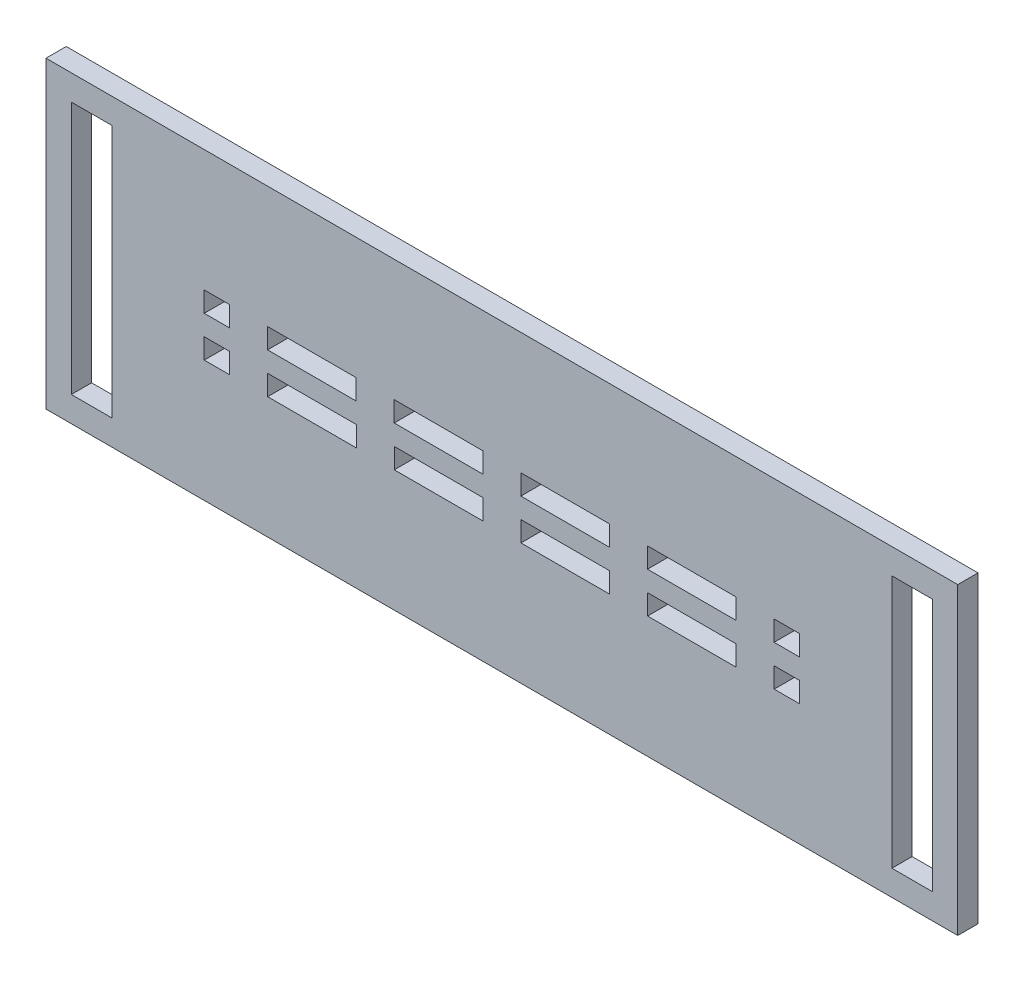
SolidWorks part; units mm, degrees
ref_plane "Ön Düzlem" through (0, 0, 0) normal (0, 0, 1) x (1, 0, 0)
ref_plane "Üst Düzlem" through (0, 0, 0) normal (0, 1, 0) x (1, 0, 0)
ref_plane "Sağ Düzlem" through (0, 0, 0) normal (1, 0, 0) x (0, 0, -1)
sketch "Çizim1" plane through (0, 0, 0) normal (0, 0, 1) x (1, 0, 0)
  line L1 (-250.4276, 53.1738) -> (109.5724, 53.1738)
  line L2 (-250.4276, 53.1738) -> (-250.4276, -66.8262)
  line L3 (-250.4276, -66.8262) -> (109.5724, -66.8262)
  line L4 (109.5724, 53.1738) -> (109.5724, -66.8262)
  line L5 (-221.5076, 5.1738) -> (80.6524, 5.1738)
  line L6 (-221.5076, 5.1738) -> (-221.5076, -2.8262)
  line L7 (-221.5076, -2.8262) -> (80.6524, -2.8262)
  line L8 (80.6524, 5.1738) -> (80.6524, -2.8262)
  line L9 (-221.5076, -10.8262) -> (80.6524, -10.8262)
  line L10 (-221.5076, -10.8262) -> (-221.5076, -18.8262)
  line L11 (-221.5076, -18.8262) -> (80.6524, -18.8262)
  line L12 (80.6524, -10.8262) -> (80.6524, -18.8262)
  dimension "D1" = 120
  dimension "D2" = 360
  dimension "D3" = 302.16
  dimension "D4" = 8
  dimension "D5" = 8
  dimension "D6" = 302.16
  dimension "D7" = 8
  dimension "D8" = 28.92
  dimension "D9" = 48
  dimension "D10" = 0
extrude "Yükseklik-Ekstrüzyon1" add sketch "Çizim1" along normal blind 8 contours L4 L1 L2 L3 L5 L8 L7 L6 L9 L12 L11 L10 | L12 L9 L10 L11 | L8 L5 L6 L7
sketch "Çizim4" plane through (0, 0, 0) normal (0, 0, -1) x (-1, 0, 0)
  line L0 (70.4276, 53.1738) -> (70.4276, 16.8788) construction
  line L1 (224.4276, 43.1738) -> (240.4276, 43.1738)
  line L2 (224.4276, 43.1738) -> (224.4276, -56.8262)
  line L3 (224.4276, -56.8262) -> (240.4276, -56.8262)
  line L4 (240.4276, 43.1738) -> (240.4276, -56.8262)
  line L5 (250.4276, 53.1738) -> (-109.5724, 53.1738) construction
  line L6 (-83.5724, 43.1738) -> (-99.5724, 43.1738)
  line L7 (-83.5724, 43.1738) -> (-83.5724, -56.8262)
  line L8 (-83.5724, -56.8262) -> (-99.5724, -56.8262)
  line L9 (-99.5724, 43.1738) -> (-99.5724, -56.8262)
extrude "Kes-Ekstrüzyon3" cut sketch "Çizim4" against normal blind 10
sketch "Çizim5" plane through (0, 0, 8) normal (0, 0, 1) x (1, 0, 0)
  line L0 (-127.9123, -10.8262) -> (-127.9123, -18.8262)
  line L1 (-187.9429, 5.1738) -> (47.0877, 5.1738)
  line L2 (-187.9429, 5.1738) -> (-187.9429, -2.8262)
  line L3 (-187.9429, -2.8262) -> (47.0877, -2.8262)
  line L4 (47.0877, 5.1738) -> (47.0877, -2.8262)
  line L5 (47.0877, -10.8262) -> (-187.9429, -10.8262)
  line L6 (47.0877, -10.8262) -> (47.0877, -18.8262)
  line L7 (47.0877, -18.8262) -> (-187.9429, -18.8262)
  line L8 (-187.9429, -10.8262) -> (-187.9429, -18.8262)
  line L9 (-177.9429, 5.1738) -> (-162.9429, 5.1738)
  line L10 (-177.9429, 5.1738) -> (-177.9429, -2.8262)
  line L11 (-177.9429, -2.8262) -> (-162.9429, -2.8262)
  line L12 (-162.9429, 5.1738) -> (-162.9429, -2.8262)
  line L13 (-177.9123, -10.8262) -> (-162.9123, -10.8262)
  line L14 (-177.9123, -10.8262) -> (-177.9123, -18.8262)
  line L15 (-177.9123, -18.8262) -> (-162.9123, -18.8262)
  line L16 (-162.9123, -10.8262) -> (-162.9123, -18.8262)
  line L17 (-127.9123, -10.8262) -> (-112.9123, -10.8262)
  line L18 (-112.9123, -10.8262) -> (-112.9123, -18.8262)
  line L19 (-127.9123, -18.8262) -> (-112.9123, -18.8262)
  line L20 (-127.9429, 5.1738) -> (-127.9429, -2.8262)
  line L21 (-127.9429, 5.1738) -> (-112.9429, 5.1738)
  line L22 (-112.9429, 5.1738) -> (-112.9429, -2.8262)
  line L23 (-127.9429, -2.8262) -> (-112.9429, -2.8262)
  line L24 (-77.9123, -10.8262) -> (-77.9123, -18.8262)
  line L25 (-77.9123, -10.8262) -> (-62.9123, -10.8262)
  line L26 (-62.9123, -10.8262) -> (-62.9123, -18.8262)
  line L27 (-77.9123, -18.8262) -> (-62.9123, -18.8262)
  line L28 (-77.9429, 5.1738) -> (-77.9429, -2.8262)
  line L29 (-77.9429, 5.1738) -> (-62.9429, 5.1738)
  line L30 (-62.9429, 5.1738) -> (-62.9429, -2.8262)
  line L31 (-77.9429, -2.8262) -> (-62.9429, -2.8262)
  line L32 (-27.9123, -10.8262) -> (-27.9123, -18.8262)
  line L33 (-27.9123, -10.8262) -> (-12.9123, -10.8262)
  line L34 (-12.9123, -10.8262) -> (-12.9123, -18.8262)
  line L35 (-27.9123, -18.8262) -> (-12.9123, -18.8262)
  line L36 (-27.9429, 5.1738) -> (-27.9429, -2.8262)
  line L37 (-27.9429, 5.1738) -> (-12.9429, 5.1738)
  line L38 (-12.9429, 5.1738) -> (-12.9429, -2.8262)
  line L39 (-27.9429, -2.8262) -> (-12.9429, -2.8262)
  line L40 (22.0877, -10.8262) -> (22.0877, -18.8262)
  line L41 (22.0877, -10.8262) -> (37.0877, -10.8262)
  line L42 (37.0877, -10.8262) -> (37.0877, -18.8262)
  line L43 (22.0877, -18.8262) -> (37.0877, -18.8262)
  line L44 (22.0571, 5.1738) -> (22.0571, -2.8262)
  line L45 (22.0571, 5.1738) -> (37.0571, 5.1738)
  line L46 (37.0571, 5.1738) -> (37.0571, -2.8262)
  line L47 (22.0571, -2.8262) -> (37.0571, -2.8262)
  dimension "D1" = 5
extrude "Kes-Ekstrüzyon4" cut sketch "Çizim5" against normal up to surface (8 mm away) contours L20 L1 L12 L3 | L5 L16 L7 L0 | L14 L5 L8 L7 | L10 L1 L2 L3 | L24 L5 L18 L7 | L28 L1 L22 L3 | L32 L5 L26 L7 | L36 L1 L30 L3 | L40 L5 L34 L7 | L44 L1 L38 L3 | L5 L42 L7 L6 | L1 L46 L3 L4 up to face at (-232.4276, -6.8262, 0)
